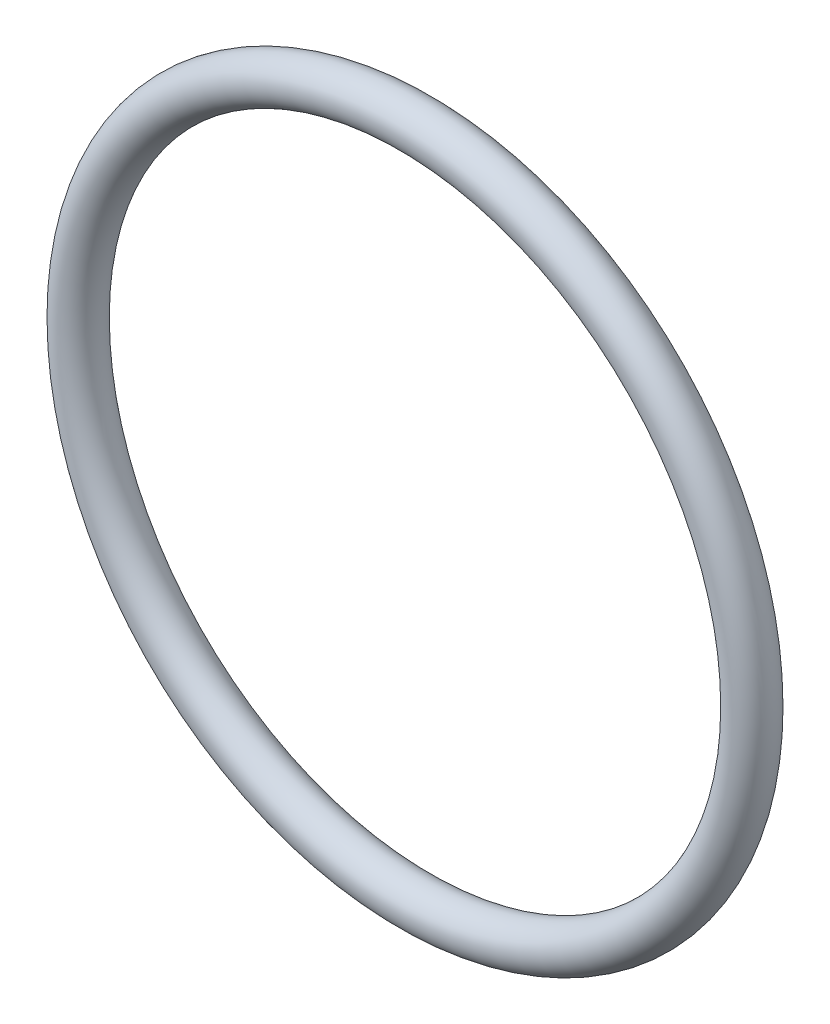
SolidWorks part; units mm, degrees
ref_plane "正面" through (0, 0, 0) normal (0, 0, 1) x (1, 0, 0)
ref_plane "平面" through (0, 0, 0) normal (0, 1, 0) x (1, 0, 0)
ref_plane "右側面" through (0, 0, 0) normal (1, 0, 0) x (0, 0, -1)
sketch "ｽｹｯﾁ1" plane through (0, 0, 0) normal (0, 0, 1) x (1, 0, 0)
  circle A0 centre (0, 0) radius 107
  dimension "D1" = 214
sweep "ｽｲｰﾌﾟ1" add path "ｽｹｯﾁ1" circular profile diameter 14 parameters "D3"=14
